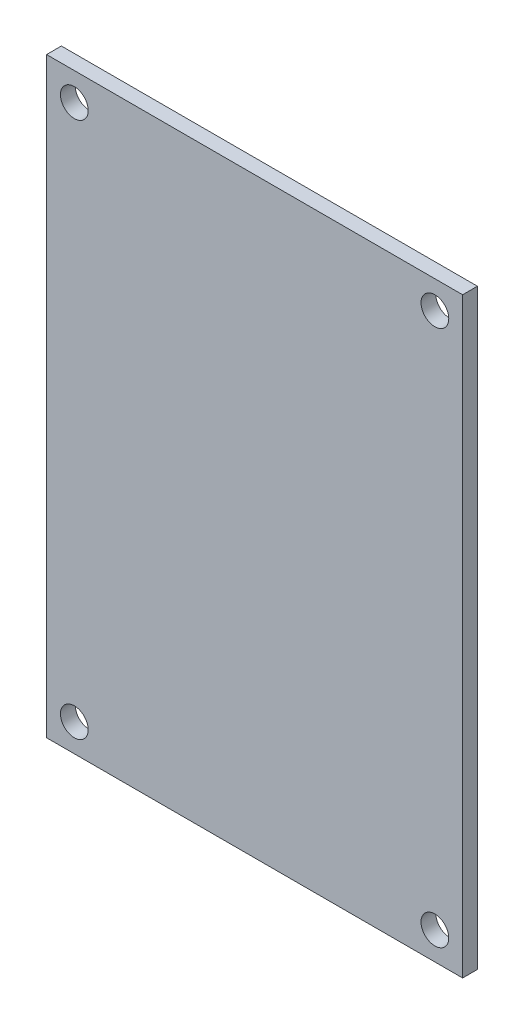
SolidWorks part; units mm, degrees
material "ABS"
ref_plane "Front Plane" through (0, 0, 0) normal (0, 0, 1) x (1, 0, 0)
ref_plane "Top Plane" through (0, 0, 0) normal (0, 1, 0) x (1, 0, 0)
ref_plane "Right Plane" through (0, 0, 0) normal (1, 0, 0) x (0, 0, -1)
ref_plane "P_board_45_x" through (0, 0, -57.4) normal (0, 0, 1) x (1, 0, 0)
sketch "Sketch1" plane through (0, 0, -57.4) normal (0, 0, 1) x (1, 0, 0)
  line L1 (-118.15, -32) -> (-73.15, -32)
  line L2 (-118.15, -32) -> (-118.15, 32)
  line L3 (-118.15, 32) -> (-73.15, 32)
  line L4 (-73.15, -32) -> (-73.15, 32)
extrude "Boss-Extrude1" add sketch "Sketch1" along normal blind 1.6
ref_plane "P_bd" through (0, 0, -57.4) normal (0, 0, 1) x (1, 0, 0)
sketch "Sketch2" plane through (0, 0, -57.4) normal (0, 0, 1) x (1, 0, 0)
  circle A0 centre (-115.15, -29) radius 1.5
  circle A1 centre (-115.15, 29) radius 1.5
  circle A2 centre (-76.15, -29) radius 1.5
  circle A3 centre (-76.15, 29) radius 1.5
extrude "Cut-Extrude2" cut sketch "Sketch2" along normal blind 1.6
